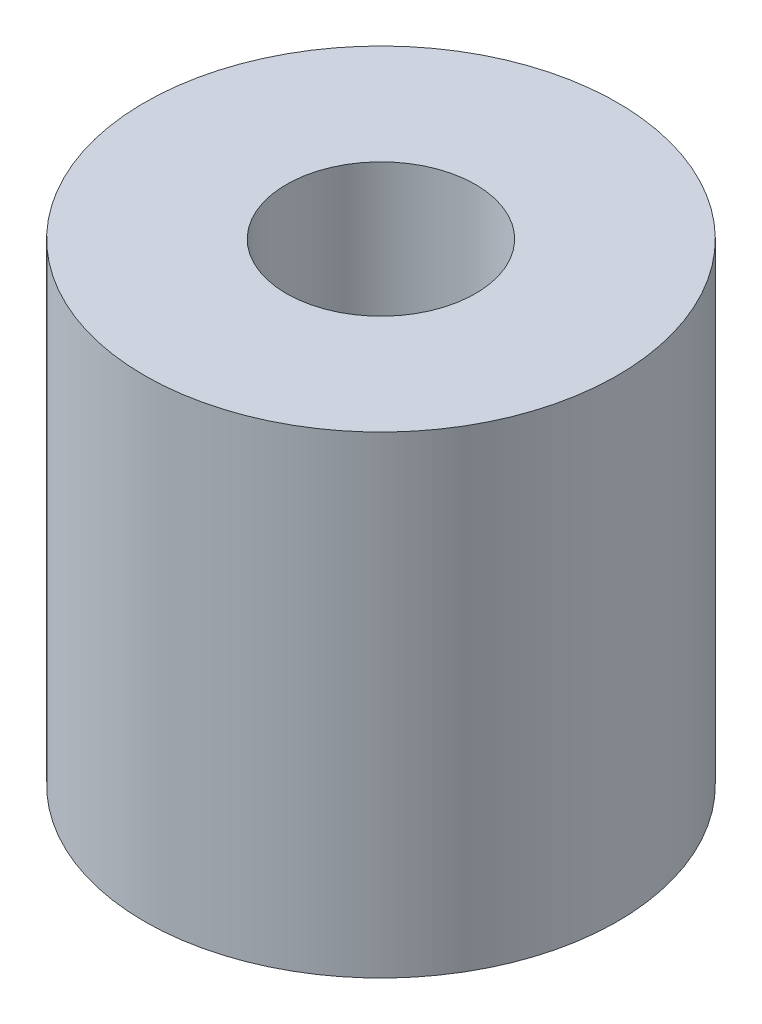
SolidWorks part; units mm, degrees
ref_plane "Front Plane" through (0, 0, 0) normal (0, 0, 1) x (1, 0, 0)
ref_plane "Top Plane" through (0, 0, 0) normal (0, 1, 0) x (1, 0, 0)
ref_plane "Right Plane" through (0, 0, 0) normal (1, 0, 0) x (0, 0, -1)
sketch "Sketch1" plane through (0, 0, 0) normal (0, 1, 0) x (1, 0, 0)
  circle A0 centre (0, 0) radius 5
  circle A1 centre (0, 0) radius 2
  dimension "D1" = 4
  dimension "D2" = 10
extrude "Boss-Extrude1" add sketch "Sketch1" along normal blind 10
